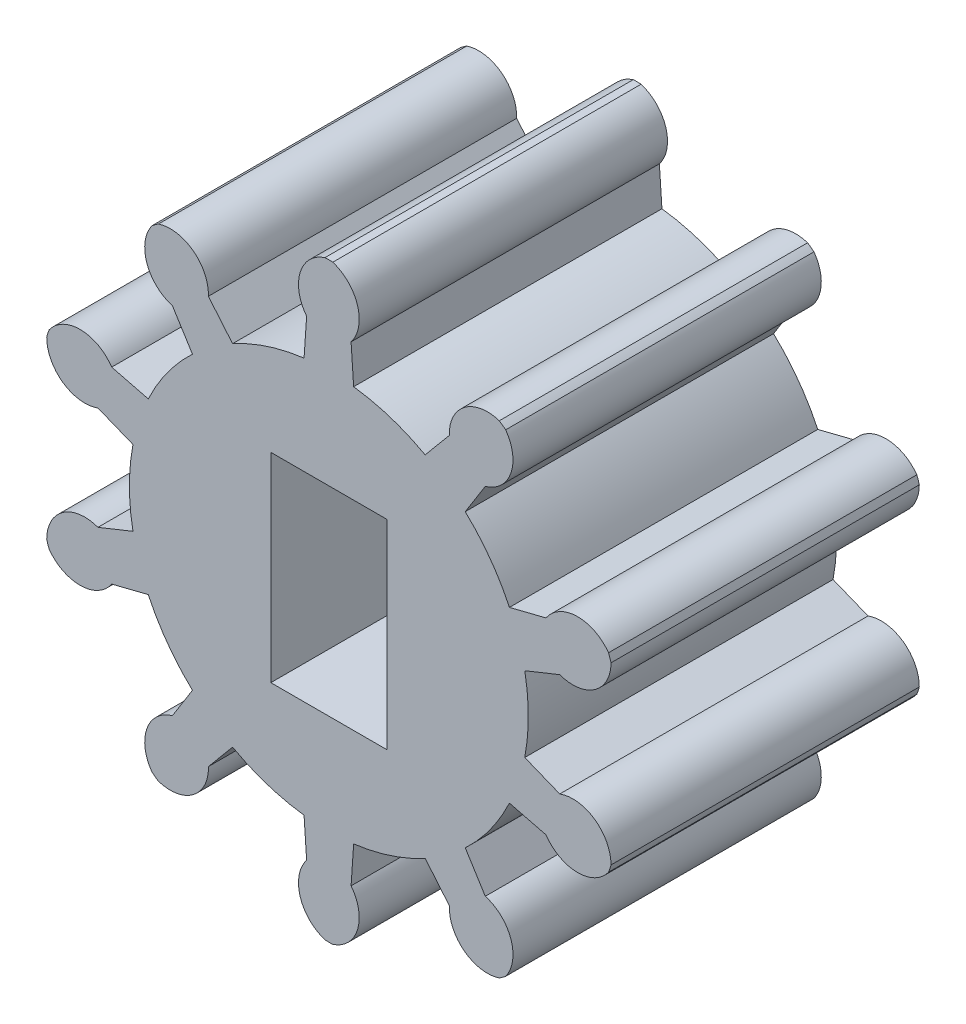
SolidWorks part; units mm, degrees
ref_plane "Front Plane" through (0, 0, 0) normal (0, 0, 1) x (1, 0, 0)
ref_plane "Top Plane" through (0, 0, 0) normal (0, 1, 0) x (1, 0, 0)
ref_plane "Right Plane" through (0, 0, 0) normal (1, 0, 0) x (0, 0, -1)
ref_plane "Plane1" through (0, 0, 20) normal (0, 0, 1) x (1, 0, 0)
ref_plane "Plane2" through (0, 0, 28.5) normal (0, 0, 1) x (1, 0, 0)
sketch "Sketch1" plane through (0, 0, 20) normal (0, 0, 1) x (1, 0, 0)
  circle A1 centre (0, 20.9252) radius 5.5
  dimension "D1" = 11
sketch "Sketch3" plane through (0, 0, 28.5) normal (0, 0, 1) x (1, 0, 0)
  line L0 (-3.9726, 20.9252) -> (15.3734, 20.9252) construction
  line L1 (0, 24.8978) -> (0, 8.7425) construction
  line L3 (-1.6, 23.6752) -> (1.6, 23.6752)
  line L4 (-1.6, 23.6752) -> (-1.6, 18.1752)
  line L5 (-1.6, 18.1752) -> (1.6, 18.1752)
  line L6 (1.6, 23.6752) -> (1.6, 18.1752)
  dimension "D1" = 3.2
  dimension "D2" = 5.5
  dimension "D3" = 1.6
  dimension "D4" = 2.75
extrude "Boss-Extrude2" add sketch "Sketch1" along normal blind 8.5
extrude "Cut-Extrude1" cut sketch "Sketch3" against normal blind 6
sketch "Sketch4" plane through (0, 0, 20) normal (0, 0, 1) x (1, 0, 0)
  line L0 (-0.6128, 27.4201) -> (-0.6835, 26.3826)
  line L1 (0, 29.0724) -> (0, 27.9031) construction
  line L2 (0.6128, 27.4201) -> (0.6835, 26.3826)
  line L3 (4.3133, 25.8195) -> (3.7607, 24.9386)
  line L4 (3.3218, 26.5399) -> (2.6548, 25.7421)
  line L5 (6.3663, 22.3494) -> (5.4015, 21.9616)
  line L6 (5.9876, 23.5151) -> (4.979, 23.2617)
  line L7 (5.9876, 18.3354) -> (4.979, 18.5888)
  line L8 (6.3663, 19.501) -> (5.4015, 19.8889)
  line L9 (3.3218, 15.3106) -> (2.6548, 16.1084)
  line L10 (4.3133, 16.031) -> (3.7607, 16.9119)
  line L11 (-0.6128, 14.4304) -> (-0.6835, 15.4679)
  line L12 (0.6128, 14.4304) -> (0.6835, 15.4679)
  line L13 (-4.3133, 16.031) -> (-3.7607, 16.9119)
  line L14 (-3.3218, 15.3106) -> (-2.6548, 16.1084)
  line L15 (-6.3663, 19.501) -> (-5.4015, 19.8889)
  line L16 (-5.9876, 18.3354) -> (-4.979, 18.5888)
  line L17 (-5.9876, 23.5151) -> (-4.979, 23.2617)
  line L18 (-6.3663, 22.3494) -> (-5.4015, 21.9616)
  line L19 (-3.3218, 26.5399) -> (-2.6548, 25.7421)
  line L20 (-4.3133, 25.8195) -> (-3.7607, 24.9386)
  circle A0 centre (0, 20.9252) radius 5.5 construction
  arc A1 (-0.6128, 27.4201) -> (-0.1088, 29.0691) centre (0.2133, 28.0692) cw
  arc A2 (-0.1088, 29.0691) -> (0.1088, 29.0691) centre (0, 27.2514) cw
  arc A3 (0.6128, 27.4201) -> (0.1088, 29.0691) centre (-0.2133, 28.0692) ccw
  arc A4 (-0.6835, 26.3826) -> (0.6835, 26.3826) centre (0, 20.9252) cw
  arc A5 (2.6548, 25.7421) -> (3.7607, 24.9386) centre (0, 20.9252) cw
  arc A6 (4.3133, 25.8195) -> (4.8749, 27.4498) centre (4.0265, 26.8301) ccw
  arc A7 (4.6988, 27.5777) -> (4.8749, 27.4498) centre (3.7184, 26.0432) cw
  arc A8 (3.3218, 26.5399) -> (4.6988, 27.5777) centre (4.3716, 26.5794) cw
  arc A9 (4.979, 23.2617) -> (5.4015, 21.9616) centre (0, 20.9252) cw
  arc A10 (6.3663, 22.3494) -> (7.7789, 23.3383) centre (6.7284, 23.3357) ccw
  arc A11 (7.7117, 23.5453) -> (7.7789, 23.3383) centre (6.0166, 22.8801) cw
  arc A12 (5.9876, 23.5151) -> (7.7117, 23.5453) centre (6.8602, 22.93) cw
  arc A13 (5.4015, 19.8889) -> (4.979, 18.5888) centre (0, 20.9252) cw
  arc A14 (5.9876, 18.3354) -> (7.7117, 18.3051) centre (6.8602, 18.9205) ccw
  arc A15 (7.7789, 18.5121) -> (7.7117, 18.3051) centre (6.0166, 18.9703) cw
  arc A16 (6.3663, 19.501) -> (7.7789, 18.5121) centre (6.7284, 18.5148) cw
  arc A17 (3.7607, 16.9119) -> (2.6548, 16.1084) centre (0, 20.9252) cw
  arc A18 (3.3218, 15.3106) -> (4.6988, 14.2727) centre (4.3716, 15.271) ccw
  arc A19 (4.8749, 14.4006) -> (4.6988, 14.2727) centre (3.7184, 15.8072) cw
  arc A20 (4.3133, 16.031) -> (4.8749, 14.4006) centre (4.0265, 15.0203) cw
  arc A21 (0.6835, 15.4679) -> (-0.6835, 15.4679) centre (0, 20.9252) cw
  arc A22 (-0.6128, 14.4304) -> (-0.1088, 12.7813) centre (0.2133, 13.7813) ccw
  arc A23 (0.1088, 12.7813) -> (-0.1088, 12.7813) centre (0, 14.5991) cw
  arc A24 (0.6128, 14.4304) -> (0.1088, 12.7813) centre (-0.2133, 13.7813) cw
  arc A25 (-2.6548, 16.1084) -> (-3.7607, 16.9119) centre (0, 20.9252) cw
  arc A26 (-4.3133, 16.031) -> (-4.8749, 14.4006) centre (-4.0265, 15.0203) ccw
  arc A27 (-4.6988, 14.2727) -> (-4.8749, 14.4006) centre (-3.7184, 15.8072) cw
  arc A28 (-3.3218, 15.3106) -> (-4.6988, 14.2727) centre (-4.3716, 15.271) cw
  arc A29 (-4.979, 18.5888) -> (-5.4015, 19.8889) centre (0, 20.9252) cw
  arc A30 (-6.3663, 19.501) -> (-7.7789, 18.5121) centre (-6.7284, 18.5148) ccw
  arc A31 (-7.7117, 18.3051) -> (-7.7789, 18.5121) centre (-6.0166, 18.9703) cw
  arc A32 (-5.9876, 18.3354) -> (-7.7117, 18.3051) centre (-6.8602, 18.9205) cw
  arc A33 (-5.4015, 21.9616) -> (-4.979, 23.2617) centre (0, 20.9252) cw
  arc A34 (-5.9876, 23.5151) -> (-7.7117, 23.5453) centre (-6.8602, 22.93) ccw
  arc A35 (-7.7789, 23.3383) -> (-7.7117, 23.5453) centre (-6.0166, 22.8801) cw
  arc A36 (-6.3663, 22.3494) -> (-7.7789, 23.3383) centre (-6.7284, 23.3357) cw
  arc A37 (-3.7607, 24.9386) -> (-2.6548, 25.7421) centre (0, 20.9252) cw
  arc A38 (-3.3218, 26.5399) -> (-4.6988, 27.5777) centre (-4.3716, 26.5794) ccw
  arc A39 (-4.8749, 27.4498) -> (-4.6988, 27.5777) centre (-3.7184, 26.0432) cw
  arc A40 (-4.3133, 25.8195) -> (-4.8749, 27.4498) centre (-4.0265, 26.8301) cw
  point P97 (0, 20.9252)
extrude "Boss-Extrude3" add sketch "Sketch4" along normal up to surface (8.5 mm away) up to face at (0, 20.9252, 28.5)
